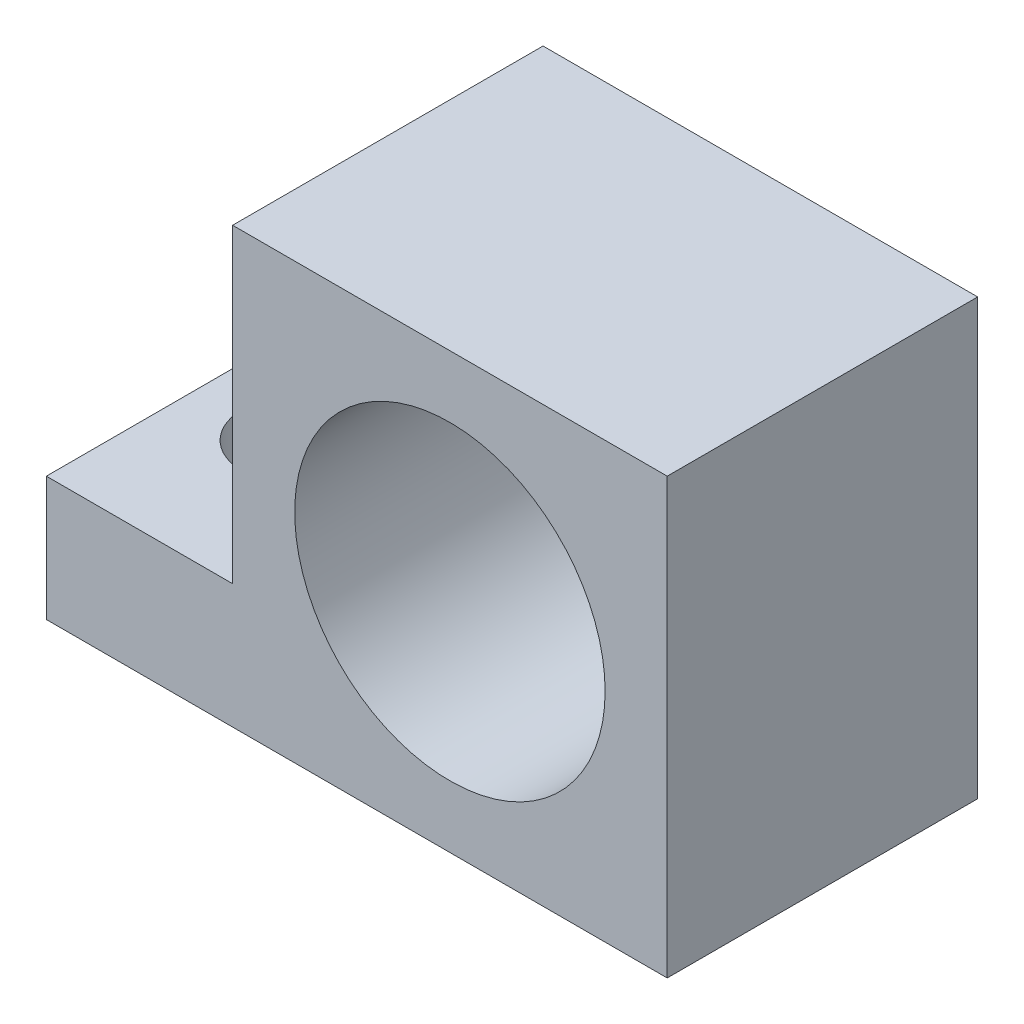
SolidWorks part; units mm, degrees
material "6061 Alloy"
ref_plane "Front Plane" through (0, 0, 0) normal (0, 0, 1) x (1, 0, 0)
ref_plane "Top Plane" through (0, 0, 0) normal (0, 1, 0) x (1, 0, 0)
ref_plane "Right Plane" through (0, 0, 0) normal (1, 0, 0) x (0, 0, -1)
sketch "Sketch1" plane through (0, 0, 0) normal (0, 0, 1) x (1, 0, 0)
  line L0 (0, 0) -> (20, 0)
  line L1 (20, 0) -> (20, 14)
  line L2 (20, 14) -> (6, 14)
  line L3 (6, 14) -> (6, 4)
  line L4 (6, 4) -> (0, 4)
  line L5 (0, 4) -> (0, 0)
  circle A0 centre (13, 7) radius 5
  point P9 (20, 7)
  point P10 (13, 14)
  dimension "D1" = 10
  dimension "D2" = 14
  dimension "D3" = 6
  dimension "D4" = 4
extrude "Boss-Extrude1" add sketch "Sketch1" along normal blind 10
hole_wizard "M3 Clearance Hole1" positions "Sketch3" profile "Sketch4" hole size "M3" standard "ISO" end condition through all
sketch "Sketch3" plane through (0, 4, 0) normal (0, 1, 0) x (-1, 0, 0)
  line L0 (-6, 10) -> (0, 10) construction
  line L1 (0, 10) -> (0, 0) construction
  point P0 (-3, 5)
  point P5 (-3, 10)
  point P8 (0, 5)
sketch "Sketch4" plane through (3, 4, 5) normal (1, 0, 0) x (0, 0, 1)
  line L0 (0, 0) -> (0, 4)
  line L1 (0, 4) -> (1.7, 4)
  line L2 (1.7, 4) -> (1.7, 0)
  line L5 (1.7, 0) -> (0, 0)
  line L11 (0, -6.35) -> (0, 107.95) construction
  dimension "Thru Hole Dia." = 3.4
  dimension "Thru Hole Depth" = 4
